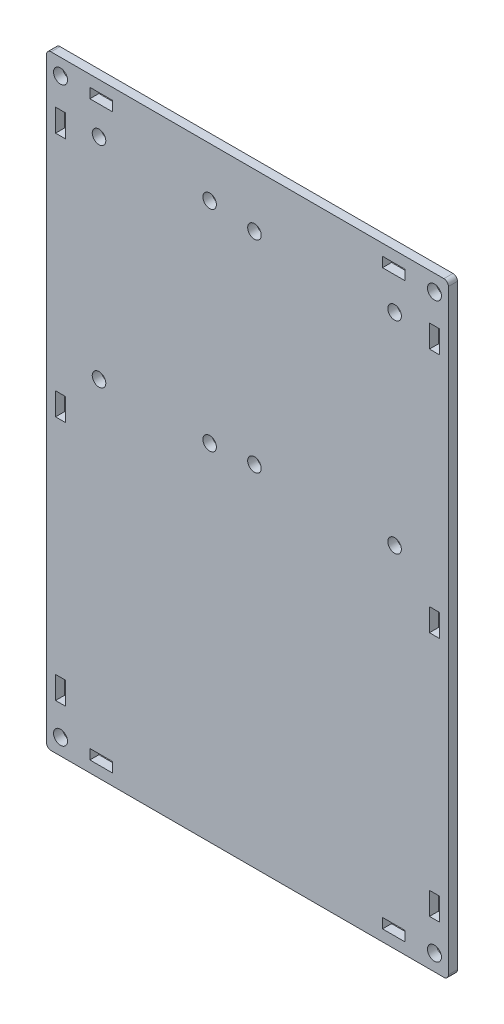
SolidWorks part; units mm, degrees
ref_plane "前基準面" through (0, 0, 0) normal (0, 0, 1) x (1, 0, 0)
ref_plane "上基準面" through (0, 0, 0) normal (0, 1, 0) x (1, 0, 0)
ref_plane "右基準面" through (0, 0, 0) normal (1, 0, 0) x (0, 0, -1)
sketch "Sketch1" plane through (0, 0, 0) normal (0, 0, 1) x (1, 0, 0)
  line L0 (-32.88, 56) -> (-44.5, 56) construction
  line L1 (-44.5, 67) -> (44.5, 67)
  line L2 (-44.5, 67) -> (-44.5, -67)
  line L3 (-44.5, -67) -> (44.5, -67)
  line L4 (44.5, 67) -> (44.5, -67)
  line L5 (-44.5, 67) -> (44.5, -67) construction
  line L6 (-44.5, -67) -> (44.5, 67) construction
  line L7 (-44.5, 56) -> (44.5, 56) construction
  line L8 (-32.88, 56) -> (-32.88, 67) construction
  line L9 (-32.88, 67) -> (-32.88, -67) construction
  line L10 (-8.38, 56) -> (-8.38, 67) construction
  line L11 (-8.38, 67) -> (-8.38, -67) construction
  line L12 (1.54, 55.08) -> (44.5, 55.08) construction
  line L13 (1.54, 55.08) -> (1.54, 67) construction
  line L14 (1.54, 67) -> (1.54, -67) construction
  line L15 (32.58, 55.08) -> (32.58, 67) construction
  line L16 (32.58, 67) -> (32.58, -67) construction
  line L17 (1.54, 10.38) -> (44.5, 10.38) construction
  line L18 (0, 0) -> (-45.154, 0) construction
  line L19 (-45.154, 0) -> (44.5, 0) construction
  line L20 (0, 0) -> (0, 67) construction
  line L21 (0, 67) -> (0, -67) construction
  line L22 (-41.4, 0) -> (-41.4, 67) construction
  line L23 (-40.3, 2.5) -> (-42.5, 2.5)
  line L24 (-40.3, 2.5) -> (-40.3, -2.5)
  line L25 (-40.3, -2.5) -> (-42.5, -2.5)
  line L26 (-42.5, 2.5) -> (-42.5, -2.5)
  line L27 (-40.3, 2.5) -> (-42.5, -2.5) construction
  line L28 (-40.3, -2.5) -> (-42.5, 2.5) construction
  line L29 (-41.4, 67) -> (-41.4, -67) construction
  line L30 (-42.5, -51.9) -> (-40.3, -51.9)
  line L31 (-42.5, 56.9) -> (-40.3, 56.9)
  line L32 (-42.5, 56.9) -> (-42.5, 51.9)
  line L33 (-42.5, 51.9) -> (-40.3, 51.9)
  line L34 (-40.3, 56.9) -> (-40.3, 51.9)
  line L35 (-42.5, 56.9) -> (-40.3, 51.9) construction
  line L36 (-42.5, 51.9) -> (-40.3, 56.9) construction
  line L37 (-40.3, -56.9) -> (-40.3, -51.9)
  line L38 (-42.5, -56.9) -> (-40.3, -56.9)
  line L39 (-42.5, -56.9) -> (-42.5, -51.9)
  line L40 (42.5, 51.9) -> (40.3, 51.9)
  line L41 (40.3, 56.9) -> (40.3, 51.9)
  line L42 (42.5, 56.9) -> (40.3, 56.9)
  line L43 (42.5, 56.9) -> (42.5, 51.9)
  line L44 (42.5, -56.9) -> (42.5, -51.9)
  line L45 (42.5, -56.9) -> (40.3, -56.9)
  line L46 (40.3, -56.9) -> (40.3, -51.9)
  line L47 (42.5, -51.9) -> (40.3, -51.9)
  line L48 (40.3, -2.5) -> (42.5, -2.5)
  line L49 (42.5, 2.5) -> (42.5, -2.5)
  line L50 (40.3, 2.5) -> (42.5, 2.5)
  line L51 (40.3, 2.5) -> (40.3, -2.5)
  line L52 (-41.4, 63.4) -> (41.4, 63.4) construction
  line L53 (34.9, 62.3) -> (29.9, 62.3)
  line L54 (-34.9, 64.5) -> (-29.9, 64.5)
  line L55 (-34.9, 64.5) -> (-34.9, 62.3)
  line L56 (-34.9, 62.3) -> (-29.9, 62.3)
  line L57 (-29.9, 64.5) -> (-29.9, 62.3)
  line L58 (-34.9, 64.5) -> (-29.9, 62.3) construction
  line L59 (-34.9, 62.3) -> (-29.9, 64.5) construction
  line L60 (29.9, 64.5) -> (29.9, 62.3)
  line L61 (34.9, 64.5) -> (29.9, 64.5)
  line L62 (34.9, 64.5) -> (34.9, 62.3)
  line L63 (34.9, -64.5) -> (34.9, -62.3)
  line L64 (34.9, -64.5) -> (29.9, -64.5)
  line L65 (29.9, -64.5) -> (29.9, -62.3)
  line L66 (34.9, -62.3) -> (29.9, -62.3)
  line L67 (-34.9, -62.3) -> (-29.9, -62.3)
  line L68 (-29.9, -64.5) -> (-29.9, -62.3)
  line L69 (-34.9, -64.5) -> (-29.9, -64.5)
  line L70 (-34.9, -64.5) -> (-34.9, -62.3)
  circle A0 centre (-32.88, 56) radius 1.5
  circle A2 centre (-8.38, 56) radius 1.5
  circle A3 centre (-32.88, 9.5) radius 1.5
  circle A4 centre (-8.38, 9.5) radius 1.5
  circle A5 centre (1.54, 55.08) radius 1.5
  circle A6 centre (32.58, 55.08) radius 1.5
  circle A7 centre (1.54, 10.38) radius 1.5
  circle A8 centre (32.58, 10.38) radius 1.5
  circle A9 centre (-41.4, 63.4) radius 1.55
  circle A10 centre (-41.4, -63.4) radius 1.55
  circle A11 centre (41.4, -63.4) radius 1.55
  circle A12 centre (41.4, 63.4) radius 1.55
  point P0 (0, 0)
  point P47 (-41.4, 0)
  point P54 (-41.4, 54.4)
  point P60 (-32.4, 63.4)
  point P81 (0, 0)
  dimension "D5" = 3
  dimension "D6" = 24.5
  dimension "D7" = 3
  dimension "D9" = 3
  dimension "D10" = 3
  dimension "D15" = 3
  dimension "D16" = 3
  dimension "D18" = 3
  dimension "D19" = 3
  dimension "D20" = 3.6
  dimension "D22" = 3.1
  dimension "D28" = 6.5
  dimension "D29" = 6.5
  dimension "D1" = 89
  dimension "D2" = 134
  dimension "D3" = 11.62
  dimension "D4" = 11
  dimension "D8" = 46.5
  dimension "D11" = 46.5
  dimension "D12" = 9.92
  dimension "D13" = 11.92
  dimension "D14" = 31.04
  dimension "D17" = 44.7
  dimension "D21" = 5
  dimension "D23" = 2.2
  dimension "D24" = 2
  dimension "D25" = 5
  dimension "D26" = 2.2
  dimension "D27" = 5
  dimension "D30" = 2.2
extrude "Boss-Extrude1" add sketch "Sketch1" along normal blind 2
fillet "Fillet1" radius 1 4 edges at (44.5, -67, 1) (44.5, 67, 1) (-44.5, 67, 1) (-44.5, -67, 1)
